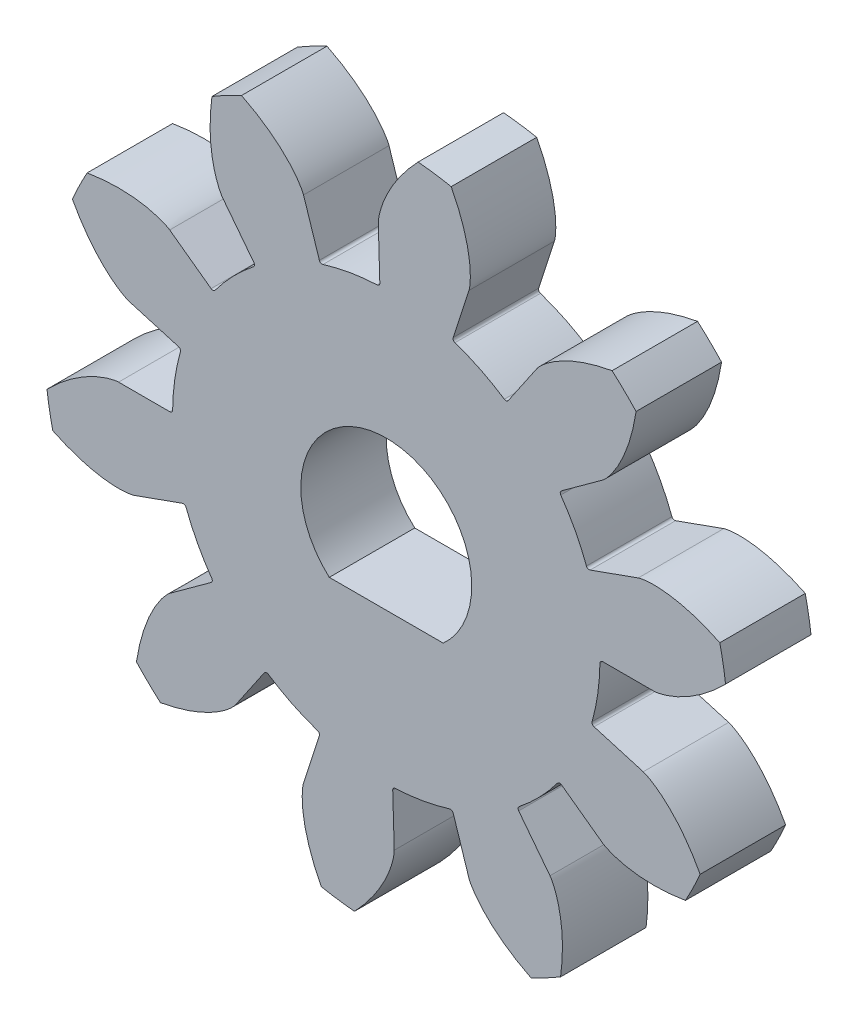
SolidWorks part; units mm, degrees
ref_plane "Front Plane" through (0, 0, 0) normal (0, 0, 1) x (1, 0, 0)
ref_plane "Top Plane" through (0, 0, 0) normal (0, 1, 0) x (1, 0, 0)
ref_plane "Right Plane" through (0, 0, 0) normal (1, 0, 0) x (0, 0, -1)
sketch "Sketch1" plane through (0, 0, 0) normal (0, 0, 1) x (1, 0, 0)
  line L0 (-2, -2.2361) -> (2, -2.2361)
  circle A0 centre (0, 0) radius 12
  arc A1 (2, -2.2361) -> (-2, -2.2361) centre (0, 0) ccw
  dimension "D1" = 24
  dimension "D2" = 6
  dimension "D3" = 4
extrude "Boss-Extrude1" add sketch "Sketch1" along normal blind 3
sketch "Sketch3" plane through (0, 0, 0) normal (0, 0, 1) x (1, 0, 0)
  line L0 (7.5, 0) -> (9.3969, 0)
  line L1 (9.0196, -2.6362) -> (7.1988, -2.104)
  line L3 (0, 0) -> (-11.8789, 1.7004) construction
  circle A0 centre (0, 0) radius 10 construction
  circle A1 centre (0, 0) radius 9.3969 construction
  arc A2 (7.1988, -2.104) -> (7.5, 0) centre (0, 0) ccw
  circle A3 centre (0, 0) radius 12 construction
  spline S0 degree 4 poles (9.3969, 0) (9.4014, 0.0001) (9.4138, 0.0005) (9.4374, 0.0023) (9.4757, 0.0065) (9.5244, 0.0137) (9.587, 0.0252) (9.6604, 0.0416) (9.7406, 0.0626) (9.8273, 0.0885) (9.9132, 0.1171) (9.9982, 0.1483) (10.0823, 0.1815) (10.1835, 0.2246) (10.3037, 0.2799) (10.4425, 0.3499) (10.5977, 0.4355) (10.7534, 0.5295) (10.9044, 0.6273) (11.0543, 0.7322) (11.1974, 0.838) (11.343, 0.954) (11.4759, 1.0642) (11.6212, 1.1942) (11.7375, 1.3011) (11.8869, 1.4488) (11.9739, 1.5381) (12.0743, 1.645) (12.1182, 1.6936) (12.1452, 1.7235) knots 0 0 0 0 0 0.005377 0.015084 0.028532 0.04661 0.064855 0.092111 0.119476 0.146842 0.174209 0.201575 0.228941 0.256307 0.307035 0.361767 0.4165 0.471232 0.525964 0.580697 0.635429 0.690161 0.744894 0.799626 0.854358 0.909091 0.954545 1 1 1 1 1 construction
  spline S1 degree 4 poles (9.3969, 0) (9.4014, 0.0001) (9.4138, 0.0005) (9.4374, 0.0023) (9.4757, 0.0065) (9.5244, 0.0137) (9.587, 0.0252) (9.6604, 0.0416) (9.7406, 0.0626) (9.8273, 0.0885) (9.9132, 0.1171) (9.9982, 0.1483) (10.0823, 0.1815) (10.1835, 0.2246) (10.3037, 0.2799) (10.4425, 0.3499) (10.5977, 0.4355) (10.7534, 0.5295) (10.9044, 0.6273) (11.0543, 0.7322) (11.1974, 0.838) (11.343, 0.954) (11.4759, 1.0642) (11.6212, 1.1942) (11.7375, 1.3011) (11.8545, 1.4168) (11.911, 1.4739) (11.9397, 1.5034) knots 0 0 0 0 0 0.005377 0.015084 0.028532 0.04661 0.064855 0.092111 0.119476 0.146842 0.174209 0.201575 0.228941 0.256307 0.307035 0.361767 0.4165 0.471232 0.525964 0.580697 0.635429 0.690161 0.744894 0.799626 0.854358 0.909091 0.909091 0.909091 0.909091 0.909091
  spline S2 degree 4 poles (9.0196, -2.6362) (9.0238, -2.6375) (9.0357, -2.6414) (9.0578, -2.6497) (9.0934, -2.6645) (9.1381, -2.685) (9.195, -2.7137) (9.2608, -2.75) (9.3319, -2.7926) (9.4078, -2.8418) (9.4822, -2.8934) (9.5551, -2.9471) (9.6266, -3.0027) (9.7116, -3.0724) (9.8115, -3.1592) (9.925, -3.2653) (10.05, -3.3911) (10.1731, -3.5249) (10.2905, -3.6611) (10.405, -3.8039) (10.5126, -3.9456) (10.6199, -4.0978) (10.7165, -4.2409) (10.8195, -4.4064) (10.9012, -4.5416) (11.0031, -4.7253) (11.0616, -4.8355) (11.128, -4.9662) (11.1564, -5.0252) (11.174, -5.0615) knots 0 0 0 0 0 0.005377 0.015084 0.028532 0.04661 0.064855 0.092111 0.119476 0.146842 0.174209 0.201575 0.228941 0.256307 0.307035 0.361767 0.4165 0.471232 0.525964 0.580697 0.635429 0.690161 0.744894 0.799626 0.854358 0.909091 0.954545 1 1 1 1 1 construction
  spline S3 degree 4 poles (9.0196, -2.6362) (9.0238, -2.6375) (9.0357, -2.6414) (9.0578, -2.6497) (9.0934, -2.6645) (9.1381, -2.685) (9.195, -2.7137) (9.2608, -2.75) (9.3319, -2.7926) (9.4078, -2.8418) (9.4822, -2.8934) (9.5551, -2.9471) (9.6266, -3.0027) (9.7116, -3.0724) (9.8115, -3.1592) (9.925, -3.2653) (10.05, -3.3911) (10.1731, -3.5249) (10.2905, -3.6611) (10.405, -3.8039) (10.5126, -3.9456) (10.6199, -4.0978) (10.7165, -4.2409) (10.8195, -4.4064) (10.9012, -4.5416) (10.981, -4.6855) (11.0192, -4.7562) (11.0384, -4.7925) knots 0 0 0 0 0 0.005377 0.015084 0.028532 0.04661 0.064855 0.092111 0.119476 0.146842 0.174209 0.201575 0.228941 0.256307 0.307035 0.361767 0.4165 0.471232 0.525964 0.580697 0.635429 0.690161 0.744894 0.799626 0.854358 0.909091 0.909091 0.909091 0.909091 0.909091
  point P5 (7.5, 0)
  point P6 (0, 0)
  point P20 (-7.1988, 2.104)
  dimension "D1" = 20
  dimension "D2" = 18.7939
  dimension "D3" = 15
  dimension "D4" = 8.146
extrude "Cut-Extrude1" cut sketch "Sketch3" against normal through all and the other way through all
fillet "Fillet2" radius 0.1 1 edges at (7.5, 0, 1.5)
fillet "Fillet4" radius 0.1 1 edges at (7.1988, -2.104, 1.5)
pattern_circular "CirPattern2" count 10 over 360 about axis through (0, 0, 3) along (0, 0, -1) of "Cut-Extrude1", "Fillet4", "Fillet2"
equation "\"P\"= 0.5'Diametral Pitch"
equation "\"N\"= 10'Number of teeth"
equation "\"phi\"= 20deg'pressure angle"
equation "\"a\"= 1 / \"P\"'addendum"
equation "\"b\"= 1.25 / \"P\"'dedendum"
equation "\"c\"= \"b\" - \"a\"'clearance"
equation "\"dp\"= \"N\" / \"P\"'pitch circle diameter"
equation "\"db\"= \"dp\" * cos ( \"phi\" )'base circle diameter"
equation "\"D1@Sketch1\"= \"dp\" + 2 * \"a\"'Addendum circle diameter"
equation "\"D1@Sketch3\"= \"dp\"'pitch circle"
equation "\"D2@Sketch3\"= \"db\" 'base circle"
equation "\"D3@Sketch3\" = \"dp\" - 2 * \"b\"'dedendum circle"
equation "\"alpha\"= sqr ( \"dp\" ^ 2 - \"db\" ^ 2 ) / \"db\" * 180 / pi - \"phi\"'alpha (deg)"
equation "\"beta\"= ( 360 / ( 4 * \"N\" ) - \"alpha\" ) * 2"
equation "\"D4@Sketch3\"= 360 / ( 4 * \"N\" ) - \"alpha\""
